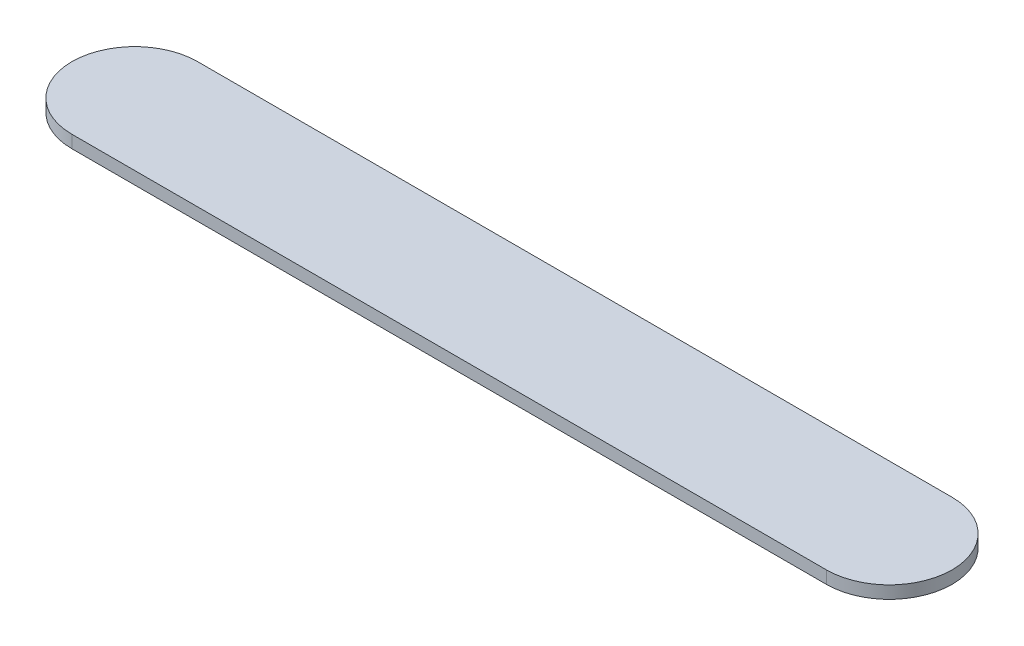
SolidWorks part; units mm, degrees
ref_plane "Front Plane" through (0, 0, 0) normal (0, 0, 1) x (1, 0, 0)
ref_plane "Top Plane" through (0, 0, 0) normal (0, 1, 0) x (1, 0, 0)
ref_plane "Right Plane" through (0, 0, 0) normal (1, 0, 0) x (0, 0, -1)
sketch "Sketch1" plane through (0, 0, 0) normal (0, 1, 0) x (1, 0, 0)
  line L0 (-47.625, 0) -> (47.625, 0) construction
  line L1 (-47.625, 7.9375) -> (47.625, 7.9375)
  line L2 (-47.625, -7.9375) -> (47.625, -7.9375)
  arc A0 (-47.625, 7.9375) -> (-47.625, -7.9375) centre (-47.625, 0) ccw
  arc A1 (47.625, -7.9375) -> (47.625, 7.9375) centre (47.625, 0) ccw
  point P3 (0, 0)
  dimension "D1" = 7.9375
  dimension "D2" = 95.25
extrude "Boss-Extrude1" add sketch "Sketch1" along normal blind 1.5875
